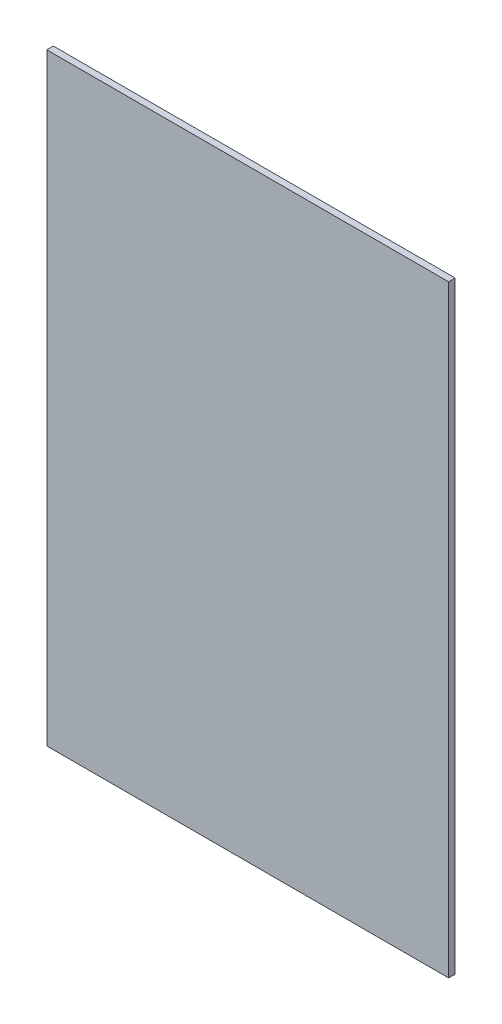
SolidWorks part; units mm, degrees
material "Polypropylene"
ref_plane "Front Plane" through (0, 0, 0) normal (0, 0, 1) x (1, 0, 0)
ref_plane "Top Plane" through (0, 0, 0) normal (0, 1, 0) x (1, 0, 0)
ref_plane "Right Plane" through (0, 0, 0) normal (1, 0, 0) x (0, 0, -1)
sketch "Sketch1" plane through (0, 0, 0) normal (0, 0, 1) x (1, 0, 0)
  line L1 (0, 0) -> (292.1, 0)
  line L2 (0, 0) -> (0, -438.15)
  line L3 (0, -438.15) -> (292.1, -438.15)
  line L4 (292.1, 0) -> (292.1, -438.15)
  dimension "D1" = 438.15
  dimension "D2" = 292.1
extrude "Boss-Extrude1" add sketch "Sketch1" along normal blind 4.7625
